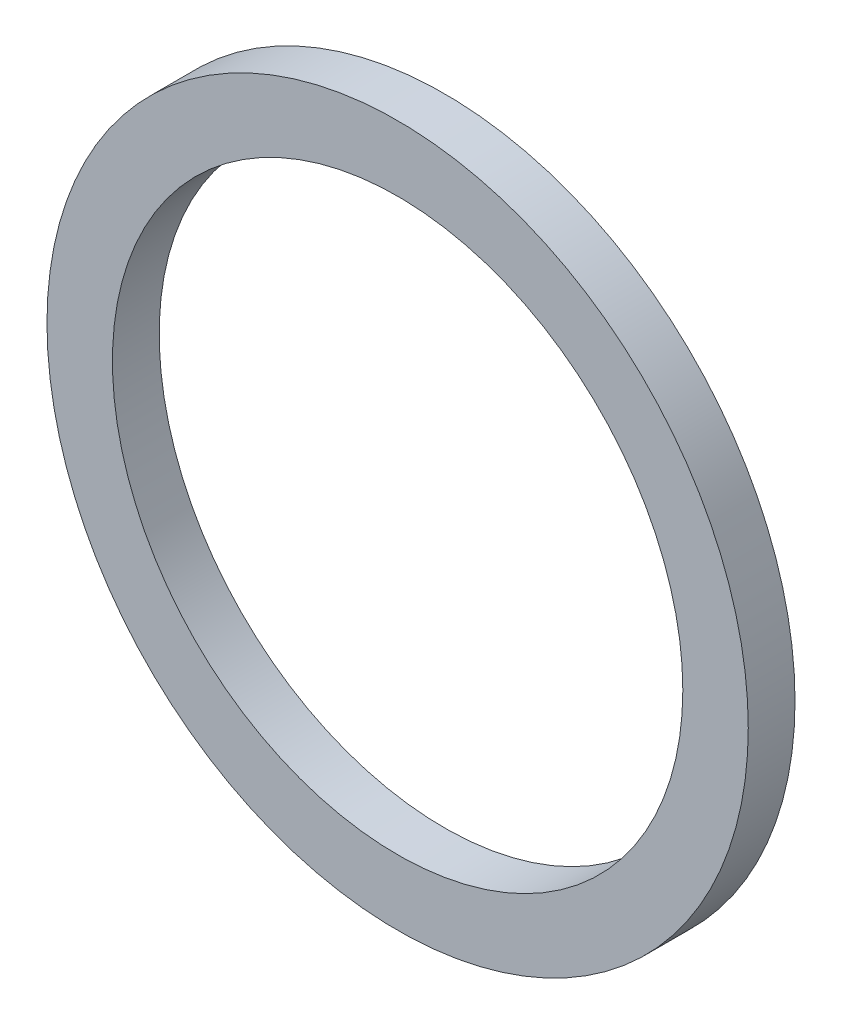
SolidWorks part; units mm, degrees
material "ABS"
ref_plane "Front" through (0, 0, 0) normal (0, 0, 1) x (1, 0, 0)
ref_plane "Top" through (0, 0, 0) normal (0, 1, 0) x (1, 0, 0)
ref_plane "Right" through (0, 0, 0) normal (1, 0, 0) x (0, 0, -1)
sketch "Эскиз1" plane through (0, 0, 0) normal (0, 0, 1) x (1, 0, 0)
  circle A0 centre (0, 0) radius 15
  circle A1 centre (0, 0) radius 12.2
  dimension "D1" = 30
  dimension "D2" = 24.4
extrude "Бобышка-Вытянуть1" add sketch "Эскиз1" along normal blind 2
